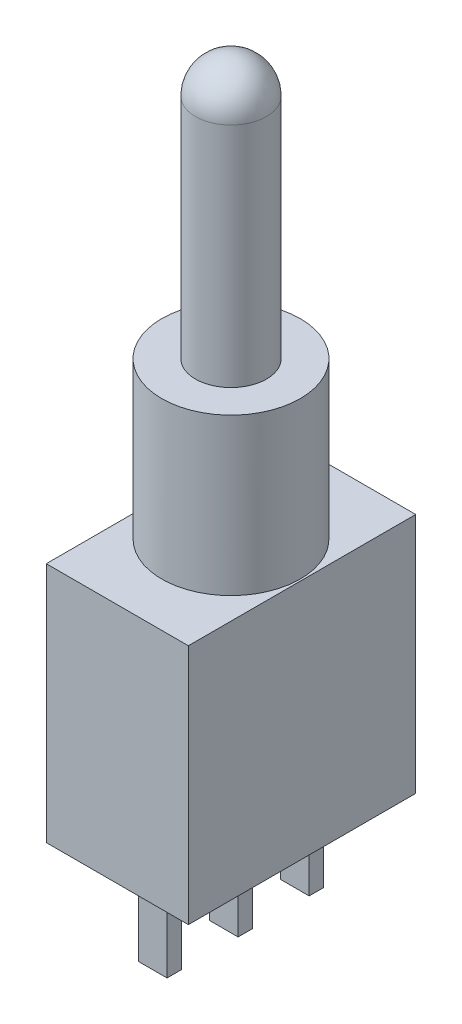
SolidWorks part; units mm, degrees
ref_plane "Front Plane" through (0, 0, 0) normal (0, 0, 1) x (1, 0, 0)
ref_plane "Top Plane" through (0, 0, 0) normal (0, 1, 0) x (1, 0, 0)
ref_plane "Right Plane" through (0, 0, 0) normal (1, 0, 0) x (0, 0, -1)
sketch "Sketch1" plane through (0, 0, 0) normal (0, 1, 0) x (1, 0, 0)
  line L1 (-2.54, -4.064) -> (2.54, -4.064)
  line L2 (-2.54, -4.064) -> (-2.54, 4.064)
  line L3 (-2.54, 4.064) -> (2.54, 4.064)
  line L4 (2.54, -4.064) -> (2.54, 4.064)
  line L5 (-2.54, -4.064) -> (2.54, 4.064) construction
  line L6 (-2.54, 4.064) -> (2.54, -4.064) construction
  point P0 (0, 0)
  dimension "D1" = 5.08
  dimension "D2" = 8.128
extrude "Boss-Extrude1" add sketch "Sketch1" along normal blind 8.636 contours L3 L4 L1 L2
sketch "Sketch2" plane through (0, 8.636, 0) normal (0, 1, 0) x (1, 0, 0)
  circle A0 centre (0, 0) radius 2.4765
  dimension "D1" = 4.953
extrude "Boss-Extrude2" add sketch "Sketch2" along normal blind 5.588
sketch "Sketch3" plane through (0, 0, 0) normal (0, -1, 0) x (1, 0, 0)
  line L0 (0, -2.54) -> (0, 0) construction
  line L1 (0.508, 0.254) -> (-0.508, 0.254)
  line L2 (0.508, 0.254) -> (0.508, -0.254)
  line L3 (0.508, -0.254) -> (-0.508, -0.254)
  line L4 (-0.508, 0.254) -> (-0.508, -0.254)
  line L5 (0.508, 0.254) -> (-0.508, -0.254) construction
  line L6 (0.508, -0.254) -> (-0.508, 0.254) construction
  line L7 (0.508, -2.286) -> (-0.508, -2.286)
  line L8 (0.508, -2.286) -> (0.508, -2.794)
  line L9 (0.508, -2.794) -> (-0.508, -2.794)
  line L10 (-0.508, -2.286) -> (-0.508, -2.794)
  line L11 (0.508, -2.286) -> (-0.508, -2.794) construction
  line L12 (0.508, -2.794) -> (-0.508, -2.286) construction
  line L13 (0.508, 2.286) -> (-0.508, 2.286)
  line L14 (0.508, 2.286) -> (0.508, 2.794)
  line L15 (0.508, 2.794) -> (-0.508, 2.794)
  line L16 (-0.508, 2.286) -> (-0.508, 2.794)
  line L17 (0.508, 2.286) -> (-0.508, 2.794) construction
  line L18 (0.508, 2.794) -> (-0.508, 2.286) construction
  line L19 (0, 0) -> (0, 2.54) construction
  line L20 (0, 2.54) -> (0, 0) construction
  point P0 (0, 0)
  point P6 (0, -2.54)
  point P11 (0, 2.54)
  point P16 (0, 0)
  dimension "D1" = 5.08
  dimension "D2" = 0.508
  dimension "D3" = 1.016
extrude "Boss-Extrude3" add sketch "Sketch3" along normal blind 3.302
sketch "Sketch4" plane through (0, 14.224, 0) normal (0, 1, 0) x (1, 0, 0)
  circle A0 centre (0, 0) radius 1.27
  dimension "D1" = 2.54
extrude "Boss-Extrude4" add sketch "Sketch4" along normal blind 9.398
fillet "Fillet1" radius 1.27 1 edges at (0, 23.622, 1.27)
